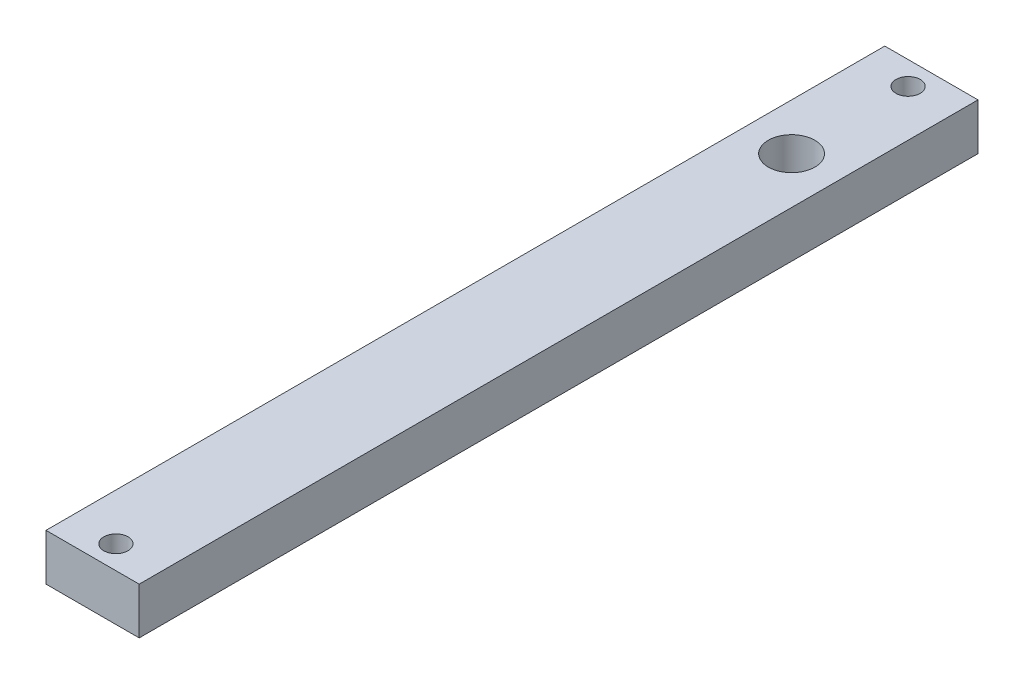
SolidWorks part; units mm, degrees
ref_plane "Front Plane" through (0, 0, 0) normal (0, 0, 1) x (1, 0, 0)
ref_plane "Top Plane" through (0, 0, 0) normal (0, 1, 0) x (1, 0, 0)
ref_plane "Right Plane" through (0, 0, 0) normal (1, 0, 0) x (0, 0, -1)
sketch "Sketch1" plane through (0, 0, 0) normal (0, 1, 0) x (1, 0, 0)
  line L1 (6.35, 50.8) -> (-6.35, 50.8)
  line L2 (6.35, 50.8) -> (6.35, -50.8)
  line L3 (6.35, -50.8) -> (-6.35, -50.8)
  line L4 (-6.35, 50.8) -> (-6.35, -50.8)
  line L5 (6.35, 50.8) -> (-6.35, -50.8) construction
  line L6 (6.35, -50.8) -> (-6.35, 50.8) construction
  line L8 (50.8, 50.8) -> (27.051, 50.8) construction
  point P0 (0, 0)
  dimension "D1" = 12.7
extrude "Boss-Extrude1" add sketch "Sketch1" along normal blind 6.35
sketch "Sketch2" plane through (0, 6.35, 0) normal (0, 1, 0) x (1, 0, 0)
  line L0 (6.35, 50.8) -> (-6.35, 50.8) construction
  line L1 (-6.35, 50.8) -> (6.35, 50.8)
  line L2 (-6.35, 50.8) -> (-6.35, 57.15)
  line L3 (-6.35, 57.15) -> (6.35, 57.15)
  line L4 (6.35, 50.8) -> (6.35, 57.15)
  line L5 (-6.35, -50.8) -> (6.35, -50.8) construction
  line L6 (-6.35, -50.8) -> (6.35, -50.8)
  line L7 (-6.35, -50.8) -> (-6.35, -57.15)
  line L8 (-6.35, -57.15) -> (6.35, -57.15)
  line L9 (6.35, -50.8) -> (6.35, -57.15)
  line L10 (-6.35, 57.15) -> (6.35, 50.8) construction
  line L11 (-6.35, -50.8) -> (6.35, -57.15) construction
  circle A0 centre (0, -53.975) radius 1.651
  circle A1 centre (0, 53.975) radius 1.651
  point P13 (0, -50.8)
  point P14 (0, -50.8)
  dimension "D3" = 3.302
  dimension "D1" = 12.7
  dimension "D2" = 6.35
extrude "Boss-Extrude2" add sketch "Sketch2" against normal up to surface (6.35 mm away) up to face at (0, 0, 0)
sketch "Sketch3" plane through (0, 6.35, 0) normal (0, 1, 0) x (1, 0, 0)
  line L2 (0, 38.1) -> (0, 53.975) construction
  circle A0 centre (0, 38.1) radius 3.175
  dimension "D1" = 6.35
  dimension "D2" = 15.875
extrude "Cut-Extrude1" cut sketch "Sketch3" against normal through all
